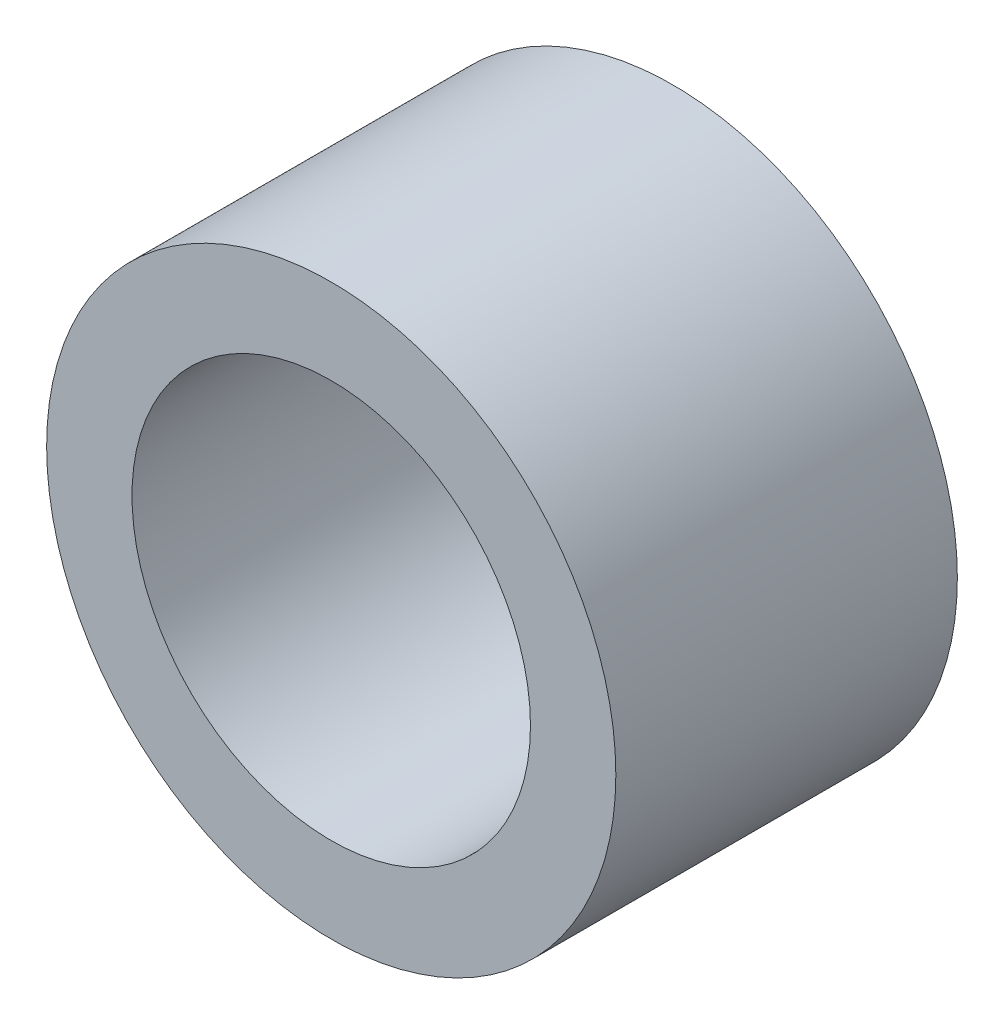
SolidWorks part; units mm, degrees
ref_plane "Front Plane" through (0, 0, 0) normal (0, 0, 1) x (1, 0, 0)
ref_plane "Top Plane" through (0, 0, 0) normal (0, 1, 0) x (1, 0, 0)
ref_plane "Right Plane" through (0, 0, 0) normal (1, 0, 0) x (0, 0, -1)
sketch "Sketch2" plane through (0, 0, 0) normal (0, 0, 1) x (1, 0, 0)
  circle A0 centre (-21.481, 16.9739) radius 10
  circle A1 centre (-21.481, 16.9739) radius 7
  dimension "D1" = 3
extrude "Boss-Extrude1" add sketch "Sketch2" along normal blind 12
scale "Scale1" scale about centroid uniform scaling yes scale factor 0.95
